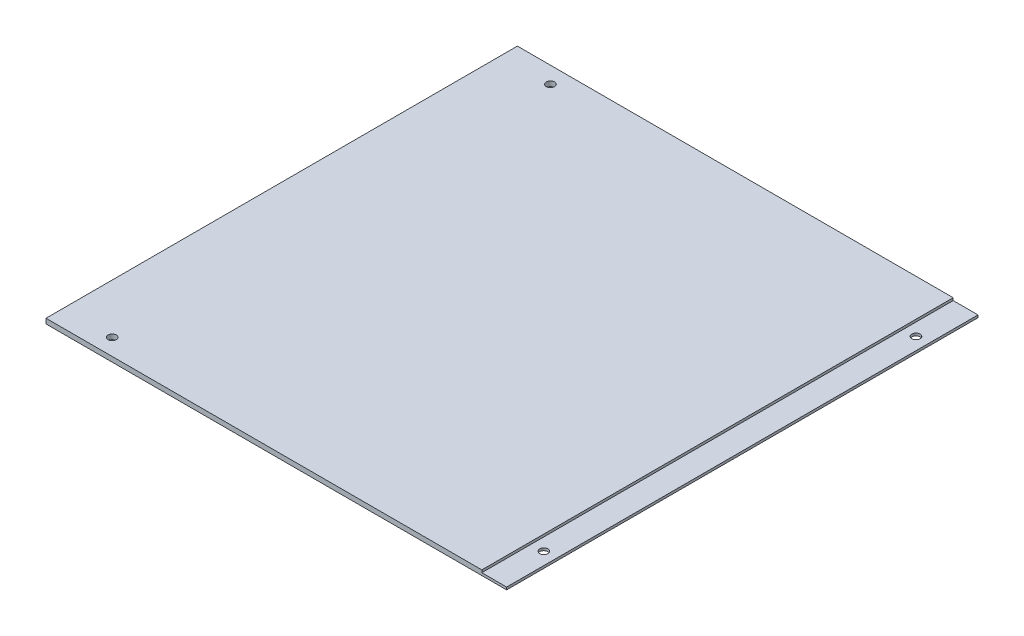
SolidWorks part; units mm, degrees
ref_plane "Front Plane" through (0, 0, 0) normal (0, 0, 1) x (1, 0, 0)
ref_plane "Top Plane" through (0, 0, 0) normal (0, 1, 0) x (1, 0, 0)
ref_plane "Right Plane" through (0, 0, 0) normal (1, 0, 0) x (0, 0, -1)
sketch "Sketch1" plane through (0, 0, 0) normal (0, 1, 0) x (1, 0, 0)
  line L1 (-139.25, 142.5) -> (139.25, 142.5)
  line L2 (-139.25, 142.5) -> (-139.25, -142.5)
  line L3 (-139.25, -142.5) -> (139.25, -142.5)
  line L4 (139.25, 142.5) -> (139.25, -142.5)
  line L5 (-139.25, 142.5) -> (139.25, -142.5) construction
  line L6 (-139.25, -142.5) -> (139.25, 142.5) construction
  point P0 (0, 0)
  dimension "D1" = 285
  dimension "D2" = 278.5
extrude "Boss-Extrude1" add sketch "Sketch1" along normal blind 3
sketch "Sketch2" plane through (0, 0, 142.5) normal (0, 0, 1) x (1, 0, 0)
  line L0 (139.25, 1.5) -> (124.25, 1.5)
  line L1 (139.25, 3) -> (139.25, 0) construction
  line L2 (124.25, 1.5) -> (124.25, 3)
  line L3 (-139.25, 3) -> (139.25, 3) construction
  line L4 (124.25, 3) -> (139.25, 3)
  line L5 (139.25, 3) -> (139.25, 1.5)
  dimension "D1" = 15
extrude "Cut-Extrude1" cut sketch "Sketch2" against normal through all
sketch "Sketch4" plane through (0, 0, 0) normal (0, -1, 0) x (1, 0, 0)
  circle A1 centre (-109.25, -132.5) radius 2.5
  circle A2 centre (-109.25, 132.5) radius 2.5
extrude "Cut-Extrude3" cut sketch "Sketch4" against normal up to next
sketch "Sketch5" plane through (0, 0, 0) normal (0, -1, 0) x (1, 0, 0)
  line L0 (139.25, 142.5) -> (139.25, -142.5) construction
  line L1 (139.25, -142.5) -> (-139.25, -142.5) construction
  line L2 (208.4943, 0) -> (-77.9078, 0) construction
  circle A0 centre (131.75, -112.5) radius 2.5
  circle A1 centre (131.75, 112.5) radius 2.5
  dimension "D1" = 5
  dimension "D2" = 7.5
  dimension "D3" = 30
extrude "Cut-Extrude4" cut sketch "Sketch5" against normal up to next
